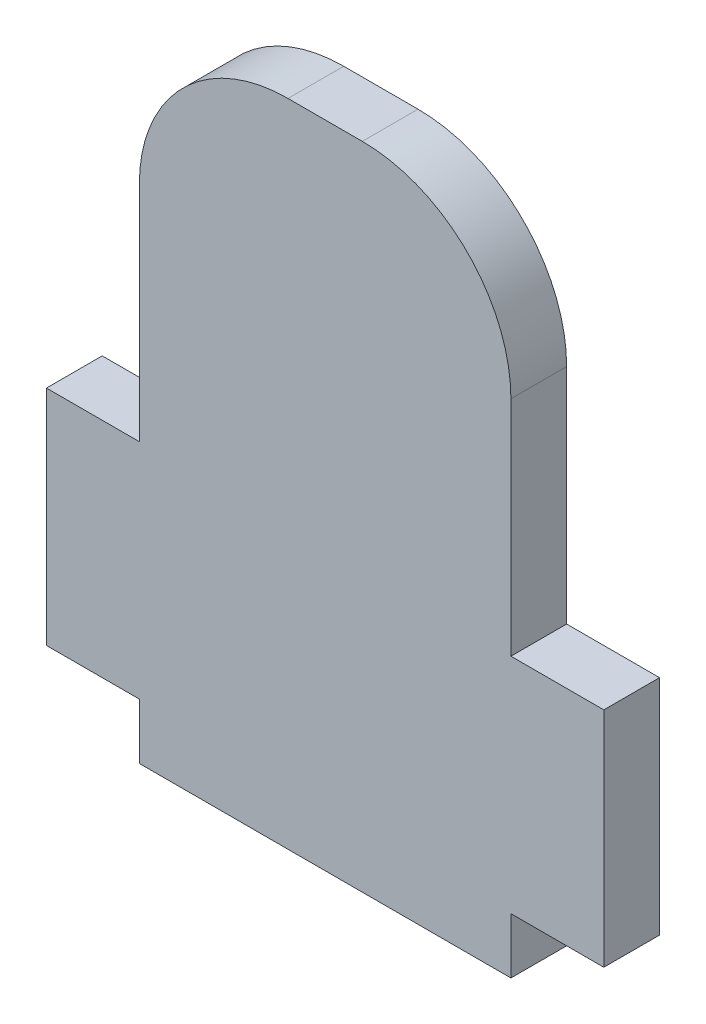
SolidWorks part; units mm, degrees
material "Balsa"
ref_plane "Alzado" through (0, 0, 0) normal (0, 0, 1) x (1, 0, 0)
ref_plane "Planta" through (0, 0, 0) normal (0, 1, 0) x (1, 0, 0)
ref_plane "Vista lateral" through (0, 0, 0) normal (1, 0, 0) x (0, 0, -1)
sketch "Croquis1" plane through (0, 0, 0) normal (0, 0, 1) x (1, 0, 0)
  line L0 (-10, -2.5) -> (-10, 9.5)
  line L1 (-10, -17.5) -> (10, -17.5)
  line L2 (-10, -17.5) -> (-10, -14.5)
  line L3 (-2, 17.5) -> (2, 17.5)
  line L4 (10, -17.5) -> (10, -14.5)
  line L5 (0, 0) -> (10, 17.5) construction
  line L6 (-10, 17.5) -> (10, -17.5) construction
  line L7 (-15, -14.5) -> (-10, -14.5)
  line L8 (-15, -14.5) -> (-15, -2.5)
  line L9 (-15, -2.5) -> (-10, -2.5)
  line L10 (15, -14.5) -> (15, -2.5)
  line L11 (10, -2.5) -> (15, -2.5)
  line L12 (10, -14.5) -> (15, -14.5)
  line L13 (10, -2.5) -> (10, 9.5)
  arc A0 (2, 17.5) -> (10, 9.5) centre (2, 9.5) cw
  arc A1 (-10, 9.5) -> (-2, 17.5) centre (-2, 9.5) cw
  point P0 (0, 0)
  dimension "D4" = 8
  dimension "D1" = 20
  dimension "D2" = 35
  dimension "D3" = 3
  dimension "D5" = 12
  dimension "D6" = 30
  dimension "D7" = 15
extrude "Saliente-Extruir1" add sketch "Croquis1" along normal blind 3
